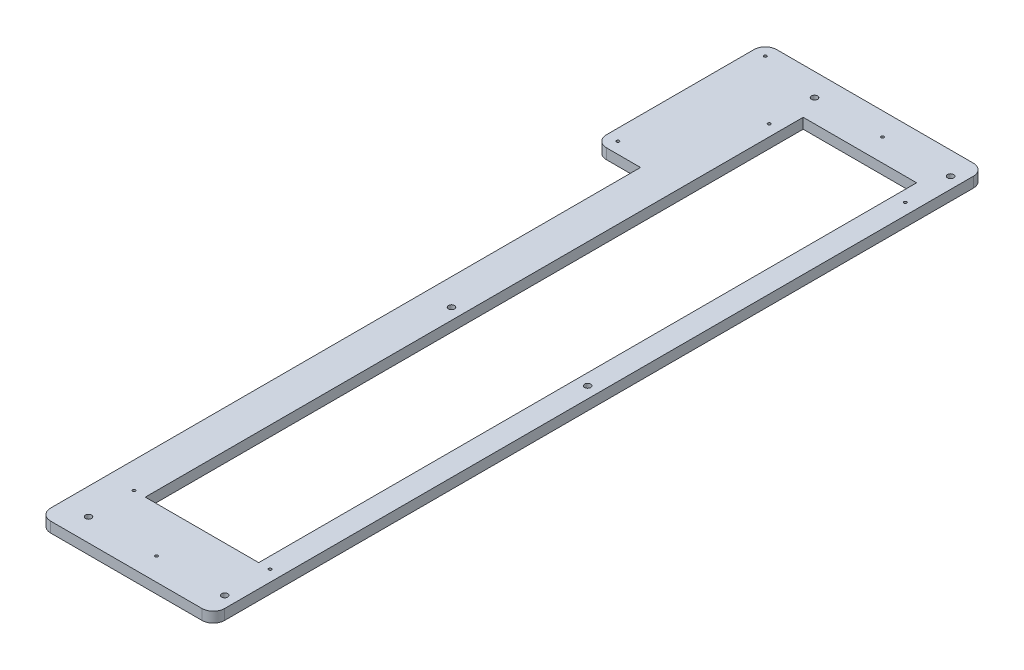
SolidWorks part; units mm, degrees
material "Acrylic (Medium-high impact)"
ref_plane "Front Plane" through (0, 0, 0) normal (0, 0, 1) x (1, 0, 0)
ref_plane "Top Plane" through (0, 0, 0) normal (0, 1, 0) x (1, 0, 0)
ref_plane "Right Plane" through (0, 0, 0) normal (1, 0, 0) x (0, 0, -1)
sketch "Sketch1" plane through (0, 0, 0) normal (0, 1, 0) x (1, 0, 0)
  line L1 (0, 0) -> (-88.9, 0)
  line L2 (0, 0) -> (0, -431.8)
  line L3 (0, -431.8) -> (-88.9, -431.8)
  line L4 (-88.9, 0) -> (-88.9, -431.8)
  dimension "D1" = 88.9
  dimension "D2" = 431.8
extrude "Boss-Extrude1" add sketch "Sketch1" along normal blind 5.8
hole_wizard "M3 Clearance Hole1" positions "Sketch6" profile "Sketch5" hole size "M3" standard "Ansi Metric" end condition through all
sketch "Sketch6" plane through (0, 5.8, 0) normal (0, 1, 0) x (-1, 0, 0)
  line L1 (0, 0) -> (88.9, 0) construction
  line L4 (44.45, 215.9) -> (88.9, 215.9) construction
  line L5 (88.9, 0) -> (88.9, 431.8) construction
  line L7 (44.45, 215.9) -> (0, 215.9) construction
  line L10 (82.55, 12.7) -> (82.55, 215.9) construction
  line L12 (6.35, 12.7) -> (6.35, 215.9) construction
  line L13 (82.55, 419.1) -> (44.45, 419.1) construction
  line L14 (44.45, 419.1) -> (6.35, 419.1) construction
  line L15 (0, 431.8) -> (0, 0) construction
  line L16 (44.45, 215.9) -> (44.45, 419.1) construction
  line L20 (82.55, 12.7) -> (6.35, 12.7) construction
  line L22 (44.45, 12.7) -> (44.45, 215.9) construction
  line L24 (44.45, 12.7) -> (44.45, 0) construction
  line L25 (82.55, 215.9) -> (82.55, 419.1) construction
  point P0 (82.55, 12.7)
  point P17 (6.35, 12.7)
  point P19 (6.35, 419.1)
  point P20 (82.55, 419.1)
  point P21 (82.55, 215.9)
  point P25 (6.35, 215.9)
  dimension "D1" = 76.2
  dimension "D2" = 12.7
  dimension "D4" = 406.4
sketch "Sketch5" plane through (-82.55, 5.8, 12.7) normal (1, 0, 0) x (0, 0, 1)
  line L0 (0, 0) -> (0, 5.8)
  line L1 (0, 5.8) -> (1.7, 5.8)
  line L2 (1.7, 5.8) -> (1.7, 0)
  line L5 (1.7, 0) -> (0, 0)
  line L11 (0, -6.35) -> (0, 107.95) construction
  dimension "Thru Hole Dia." = 3.4
  dimension "Thru Hole Depth" = 5.8
sketch "Sketch2" plane through (0, 5.8, 0) normal (0, 1, 0) x (1, 0, 0)
  line L1 (-44.45, -393.7) -> (-44.45, -25.4) construction
  line L2 (0, 0) -> (-88.9, 0) construction
  line L3 (-44.45, -209.55) -> (-88.9, -209.55) construction
  line L5 (-76.2, -25.4) -> (-12.7, -25.4)
  line L6 (-44.45, -209.55) -> (0, -209.55) construction
  line L8 (-76.2, -25.4) -> (-76.2, -393.7)
  line L9 (-76.2, -393.7) -> (-12.7, -393.7)
  line L10 (-12.7, -25.4) -> (-12.7, -393.7)
  line L11 (-88.9, 0) -> (-88.9, -431.8) construction
  line L12 (0, -431.8) -> (0, 0) construction
  dimension "D2" = 368.3
  dimension "D1" = 63.5
  dimension "D3" = 25.4
sketch "Sketch3" plane through (0, 5.8, 0) normal (0, 1, 0) x (-1, 0, 0)
  line L0 (88.9, 431.8) -> (0, 431.8) construction
  line L1 (88.9, 0) -> (97.4, 0)
  line L2 (88.9, 0) -> (88.9, 431.8)
  line L3 (88.9, 431.8) -> (97.4, 431.8)
  line L4 (97.4, 0) -> (97.4, 431.8)
  dimension "D1" = 8.5
extrude "Cut-Extrude1" cut sketch "Sketch2" against normal through all
sketch "Sketch7" plane through (0, 5.8, 0) normal (0, 1, 0) x (1, 0, 0)
  line L0 (-82.55, -12.7) -> (-6.35, -12.7) construction
  line L1 (-82.55, -215.9) -> (-6.35, -215.9) construction
  line L2 (-44.45, -25.4) -> (-44.45, -393.7) construction
  line L3 (-12.7, -25.4) -> (-76.2, -25.4) construction
  line L4 (-76.2, -393.7) -> (-12.7, -393.7) construction
  line L5 (-82.55, -12.7) -> (-82.55, -215.9) construction
  line L6 (-6.35, -12.7) -> (-6.35, -215.9) construction
  line L7 (-82.55, -38.1) -> (-6.35, -38.1) construction
  line L8 (-82.55, -393.7) -> (-6.35, -393.7) construction
  line L9 (-44.45, -393.7) -> (-44.45, -419.1) construction
  line L10 (-44.45, -419.1) -> (-44.45, -431.8) construction
  line L11 (-88.9, -431.8) -> (0, -431.8) construction
  line L12 (-82.55, -215.9) -> (-82.55, -393.7) construction
  circle A0 centre (-44.45, -12.7) radius 0.7937
  circle A1 centre (-82.55, -38.1) radius 0.7937
  circle A2 centre (-6.35, -38.1) radius 0.7938
  circle A3 centre (-6.35, -393.7) radius 0.7938
  circle A4 centre (-82.55, -393.7) radius 0.7937
  circle A5 centre (-44.45, -419.1) radius 0.7938
  dimension "D1" = 1.5875
  dimension "D2" = 25.4
  dimension "D3" = 25.4
  dimension "D4" = 355.6
extrude "Boss-Extrude2" add sketch "Sketch3" against normal through all
extrude "Cut-Extrude2" cut sketch "Sketch7" against normal through all
sketch "Sketch9" plane through (0, 5.8, 0) normal (0, 1, 0) x (1, 0, 0)
  line L1 (-97.4, 0) -> (-122.8, 0)
  line L2 (-97.4, 0) -> (-97.4, -95.25)
  line L3 (-97.4, -95.25) -> (-122.8, -95.25)
  line L4 (-122.8, 0) -> (-122.8, -95.25)
  dimension "D1" = 25.4
  dimension "D2" = 95.25
extrude "Boss-Extrude3" add sketch "Sketch9" against normal through all
sketch "Sketch10" plane through (0, 5.8, 0) normal (0, 1, 0) x (1, 0, 0)
  line L1 (-116.45, 0) -> (-116.45, -95.25) construction
  line L2 (0, 0) -> (-122.8, 0) construction
  line L3 (-122.8, -95.25) -> (-97.4, -95.25) construction
  line L4 (-122.8, 0) -> (-122.8, -95.25) construction
  circle A0 centre (-116.45, -88.9) radius 0.7937
  circle A1 centre (-116.45, -6.35) radius 0.7937
  dimension "D1" = 6.35
  dimension "D2" = 6.35
  dimension "D3" = 1.5875
  dimension "D4" = 6.35
extrude "Cut-Extrude4" cut sketch "Sketch10" against normal through all
fillet "Fillet1" radius 6.35 5 edges at (0, 2.9, 431.8) (-97.4, 2.9, 431.8) (-122.8, 2.9, 95.25) (0, 2.9, 0) (-122.8, 2.9, 0)
